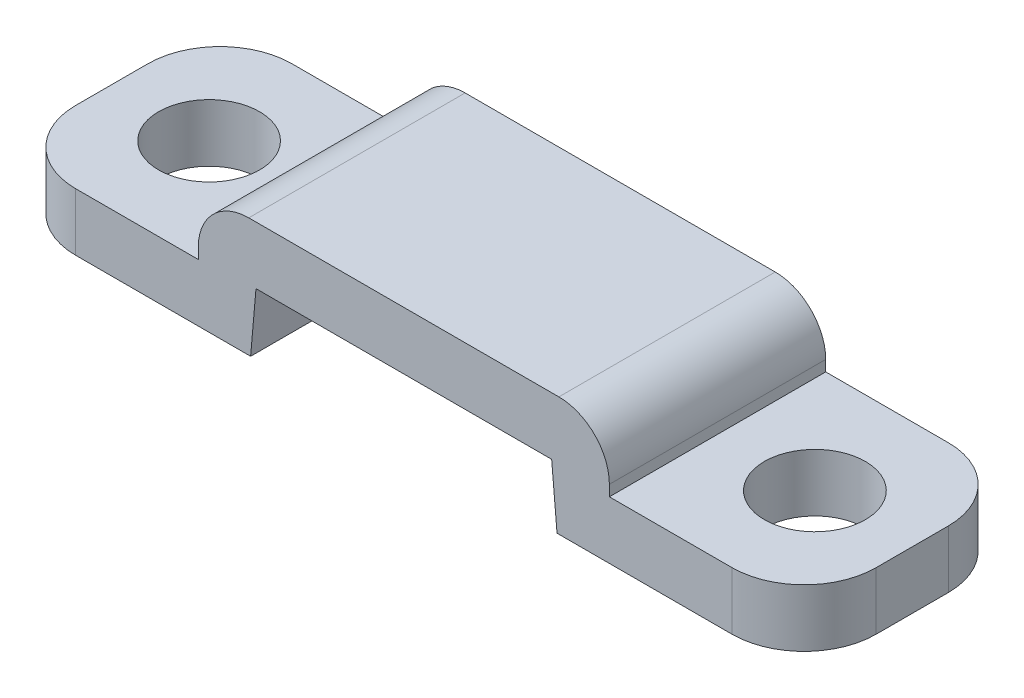
SolidWorks part; units mm, degrees
ref_plane "Front Plane" through (0, 0, 0) normal (0, 0, 1) x (1, 0, 0)
ref_plane "Top Plane" through (0, 0, 0) normal (0, 1, 0) x (1, 0, 0)
ref_plane "Right Plane" through (0, 0, 0) normal (1, 0, 0) x (0, 0, -1)
sketch "Sketch1" plane through (0, 0, 0) normal (0, 0, 1) x (1, 0, 0)
  line L0 (-7.239, 0.9525) -> (-7.239, 3.1115)
  line L1 (-5.207, 1.0795) -> (5.207, 1.0795)
  line L2 (-5.207, 1.0795) -> (-5.207, -1.0795)
  line L4 (5.207, 1.0795) -> (5.207, -1.0795)
  line L5 (-5.207, 1.0795) -> (5.207, -1.0795) construction
  line L6 (-5.207, -1.0795) -> (5.207, 1.0795) construction
  line L7 (-7.239, 3.1115) -> (7.239, 3.1115)
  line L8 (7.239, 3.1115) -> (7.239, 0.9525)
  line L9 (5.207, -1.0795) -> (14.097, -1.0795)
  line L10 (-5.207, -1.0795) -> (-14.097, -1.0795)
  line L11 (-14.097, -1.0795) -> (-14.097, 0.9525)
  line L12 (-14.097, 0.9525) -> (-7.239, 0.9525)
  line L13 (14.097, -1.0795) -> (14.097, 0.9525)
  line L14 (14.097, 0.9525) -> (7.239, 0.9525)
  point P0 (0, 0)
  dimension "D1" = 10.414
  dimension "D2" = 2.159
  dimension "D3" = 2.032
  dimension "D4" = 2.032
  dimension "D5" = 2.032
  dimension "D6" = 8.89
extrude "Boss-Extrude1" add sketch "Sketch1" along normal blind 7.62
sketch "Sketch2" plane through (0, 0.9525, 0) normal (0, 1, 0) x (1, 0, 0)
  line L0 (-10.668, 0) -> (-10.668, -7.62) construction
  line L1 (-7.239, 0) -> (-14.097, 0) construction
  line L2 (-7.239, -7.62) -> (-14.097, -7.62) construction
  line L3 (10.668, 0) -> (10.668, -7.62) construction
  line L4 (14.097, 0) -> (7.239, 0) construction
  line L5 (14.097, -7.62) -> (7.239, -7.62) construction
  circle A0 centre (-10.668, -3.81) radius 1.778
  circle A1 centre (10.668, -3.81) radius 1.778
  dimension "D1" = 3.556
extrude "Cut-Extrude1" cut sketch "Sketch2" against normal through all
fillet "Fillet1" radius 2.54 4 edges at (14.097, -0.0635, 7.62) (14.097, -0.0635, 0) (-14.097, -0.0635, 0) (-14.097, -0.0635, 7.62)
fillet "Fillet2" radius 1.778 2 edges at (7.239, 3.1115, 3.81) (-7.239, 3.1115, 3.81)
draft "Draft1" type of draft neutral plane draft angle 5 faces to draft 2 face at (5.207, 0, 3.81) face at (-5.207, 0, 3.81) neutral plane through (-5.207, 1.0795, 7.62) neutral plane normal (0, -1, 0) parameters "D1"=5
